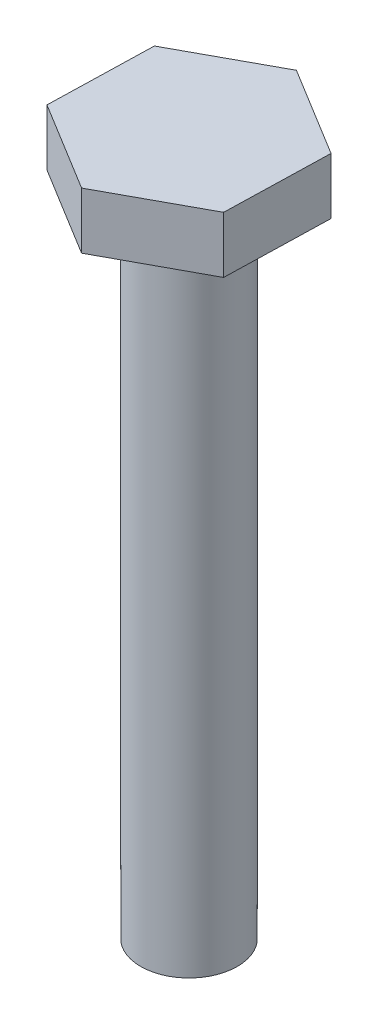
SolidWorks part; units mm, degrees
ref_plane "Front Plane" through (0, 0, 0) normal (0, 0, 1) x (1, 0, 0)
ref_plane "Top Plane" through (0, 0, 0) normal (0, 1, 0) x (1, 0, 0)
ref_plane "Right Plane" through (0, 0, 0) normal (1, 0, 0) x (0, 0, -1)
sketch "Sketch1" plane through (0, 0, 0) normal (0, 1, 0) x (1, 0, 0)
  line L1 (5.5434, -3.3943) -> (5.7112, 3.1035)
  line L2 (5.7112, 3.1035) -> (0.1679, 6.4978)
  line L3 (0.1679, 6.4978) -> (-5.5434, 3.3943)
  line L4 (-5.5434, 3.3943) -> (-5.7112, -3.1035)
  line L5 (-5.7112, -3.1035) -> (-0.1679, -6.4978)
  line L6 (-0.1679, -6.4978) -> (5.5434, -3.3943)
  circle A0 centre (0, 0) radius 5.6292 construction
extrude "Boss-Extrude1" add sketch "Sketch1" along normal blind 3.5
sketch "Sketch2" plane through (0, 0, 0) normal (0, -1, 0) x (1, 0, 0)
  circle A0 centre (0, 0) radius 3
extrude "Boss-Extrude2" add sketch "Sketch2" along normal blind 40
